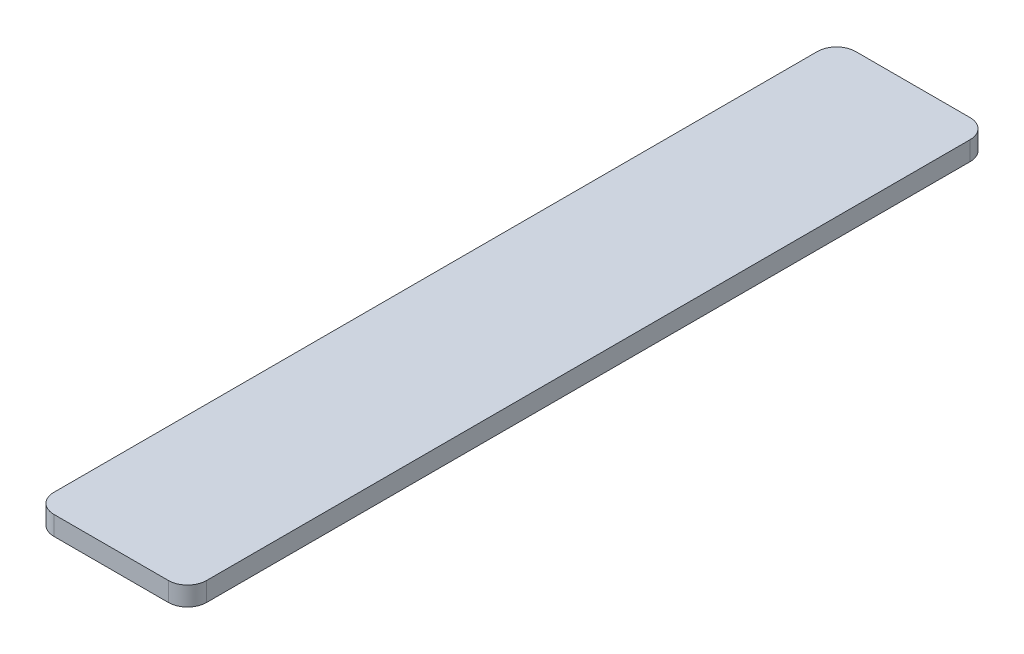
SolidWorks part; units mm, degrees
ref_plane "Front Plane" through (0, 0, 0) normal (0, 0, 1) x (1, 0, 0)
ref_plane "Top Plane" through (0, 0, 0) normal (0, 1, 0) x (1, 0, 0)
ref_plane "Right Plane" through (0, 0, 0) normal (1, 0, 0) x (0, 0, -1)
sketch "Sketch1" plane through (0, 0, 0) normal (0, 0, 1) x (1, 0, 0)
  line L0 (0, 1.5875) -> (0, -1.5875)
  line L1 (-12.7, 0) -> (12.7, 0) construction
  point P6 (0, 0)
  dimension "Width" = 25.4
  dimension "Thk" = 3.175
sketch "Sketch2" plane through (0, 0, 0) normal (1, 0, 0) x (0, 0, -1)
  line L0 (66.675, 0) -> (-66.675, 0)
  point P4 (0, 0)
  dimension "Length" = 133.35
sketch "Sketch3" plane through (0, 0, 0) normal (0, 0, 1) x (1, 0, 0)
  line L1 (12.7, 1.5875) -> (-12.7, 1.5875)
  line L2 (12.7, 1.5875) -> (12.7, -1.5875)
  line L3 (12.7, -1.5875) -> (-12.7, -1.5875)
  line L4 (-12.7, 1.5875) -> (-12.7, -1.5875)
  line L5 (12.7, 1.5875) -> (-12.7, -1.5875) construction
  line L6 (12.7, -1.5875) -> (-12.7, 1.5875) construction
  point P0 (0, 0)
extrude "Boss-Extrude1" add sketch "Sketch3" along normal up to vertex (66.675 mm away) and the other way up to vertex (66.675 mm away) up to point (0, 0, 66.675) other way up to point (0, 0, -66.675)
sketch "Sketch4" plane through (0, 1.5875, 0) normal (0, 1, 0) x (1, 0, 0)
  line L4 (12.7, -66.675) -> (12.7, 66.675)
  line L5 (12.7, 66.675) -> (-12.7, 66.675)
  line L6 (-12.7, 66.675) -> (-12.7, -66.675)
  line L7 (-12.7, -66.675) -> (12.7, -66.675)
  line L8 (12.7, -63.5) -> (12.7, 63.5)
  line L9 (9.525, 66.675) -> (-9.525, 66.675)
  line L10 (-12.7, 63.5) -> (-12.7, -63.5)
  line L11 (-9.525, -66.675) -> (9.525, -66.675)
  arc A0 (-12.7, -63.5) -> (-9.525, -66.675) centre (-9.525, -63.5) ccw
  arc A1 (12.7, -63.5) -> (9.525, -66.675) centre (9.525, -63.5) cw
  arc A2 (12.7, 63.5) -> (9.525, 66.675) centre (9.525, 63.5) ccw
  arc A3 (-9.525, 66.675) -> (-12.7, 63.5) centre (-9.525, 63.5) ccw
  dimension "D2" = 3.175
  dimension "D1" = 0
extrude "Cut-Extrude1" cut sketch "Sketch4" against normal through all flip side to cut
